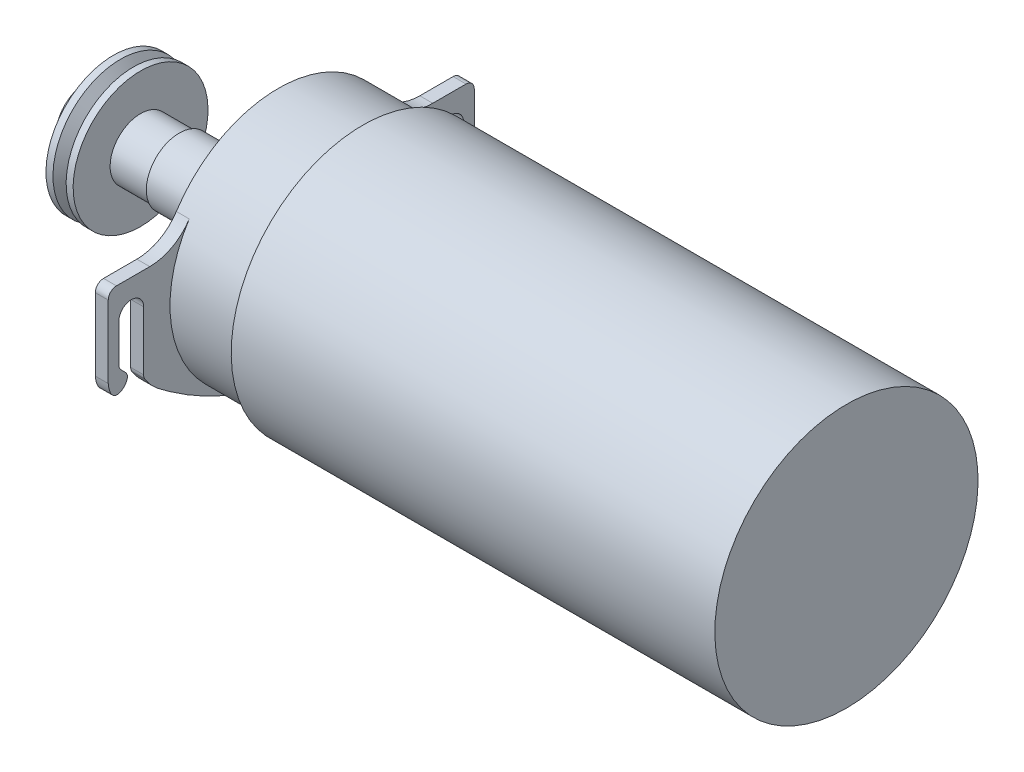
SolidWorks part; units mm, degrees
ref_plane "Front Plane" through (0, 0, 0) normal (0, 0, 1) x (1, 0, 0)
ref_plane "Top Plane" through (0, 0, 0) normal (0, 1, 0) x (1, 0, 0)
ref_plane "Right Plane" through (0, 0, 0) normal (1, 0, 0) x (0, 0, -1)
sketch "Sketch1" plane through (0, 0, 0) normal (0, 0, 1) x (1, 0, 0)
  line L0 (-102.8632, 0.1165) -> (65.8825, 0.1165) construction
  line L1 (65.8825, 0.1165) -> (65.8825, 40.7565)
  line L2 (65.8825, 40.7565) -> (-83.4695, 40.7565)
  line L3 (-83.4695, 40.7565) -> (-83.4695, 37.5561)
  line L4 (-83.4695, 37.5561) -> (-109.5553, 37.5561)
  line L5 (-109.5553, 37.5561) -> (-109.5553, 10.2765)
  line L6 (-109.5553, 10.2765) -> (-140.1623, 10.2765)
  line L7 (-140.1623, 10.2765) -> (-140.1623, 9.5145)
  line L8 (-140.1623, 9.5145) -> (-152.1003, 9.5145)
  line L9 (-152.1003, 9.5145) -> (-152.1003, 20.9445)
  line L10 (-152.1003, 20.9445) -> (-154.2593, 20.9445)
  line L11 (-154.2593, 20.9445) -> (-156.2913, 17.8965)
  line L12 (-156.2913, 27.6325) -> (-156.2913, 11.1433) construction
  line L13 (65.8825, 0.1165) -> (-168.8643, 0.1165)
  line L14 (-160.4823, 9.5145) -> (-160.4823, 20.9445)
  line L15 (-160.4823, 20.9445) -> (-158.3233, 20.9445)
  line L16 (-158.3233, 20.9445) -> (-156.2913, 17.8965)
  line L18 (-160.4823, 9.5145) -> (-162.6413, 9.5145)
  line L19 (-162.6413, 9.5145) -> (-164.6733, 6.4665)
  line L20 (-164.6733, 6.4665) -> (-164.6733, 11.1433) construction
  line L21 (-168.8643, 9.5145) -> (-168.8643, 0.1165)
  line L22 (-168.8643, 9.5145) -> (-166.7053, 9.5145)
  line L23 (-166.7053, 9.5145) -> (-164.6733, 6.4665)
  line L24 (-168.8643, 0.1165) -> (-98.8754, 0.1165) construction
  dimension "D1" = 40.64
  dimension "D2" = 149.352
  dimension "D3" = 26.0858
  dimension "D4" = 20.828
  dimension "D5" = 37.4396
  dimension "D6" = 44.704
  dimension "D7" = 11.938
  dimension "D8" = 2.159
  dimension "D9" = 4.064
  dimension "D11" = 11.43
  dimension "D12" = 10.16
  dimension "D13" = 2.159
  dimension "D14" = 4.064
  dimension "D15" = 3.048
  dimension "D16" = 3.048
revolve "Revolve3" add sketch "Sketch1" angle 360 about L24
sketch "Sketch3" plane through (-109.5553, 0, 0) normal (-1, 0, 0) x (0, 0, 1)
  line L0 (43.6888, 13.7026) -> (53.975, 13.7026)
  line L1 (56.515, 11.1626) -> (56.515, -11.1539)
  line L2 (53.213, -7.8364) -> (53.213, 3.9053)
  line L3 (45.593, 3.9053) -> (45.593, -14.2762)
  line L4 (0, 0.1165) -> (0, 21.1295) construction
  line L5 (-45.593, 3.9053) -> (-45.593, -14.2762)
  line L6 (-53.213, -7.8364) -> (-53.213, 3.9053)
  line L7 (-56.515, 11.1626) -> (-56.515, -11.1539)
  line L8 (-43.6888, 13.7026) -> (-53.975, 13.7026)
  arc A0 (-10.0759, -35.9418) -> (10.0759, -35.9418) centre (0, 0.1165) ccw
  arc A1 (43.6888, 13.7026) -> (31.4944, 20.3606) centre (43.6888, 28.1989) cw
  arc A2 (53.975, 13.7026) -> (56.515, 11.1626) centre (53.975, 11.1626) cw
  arc A3 (53.213, 3.9053) -> (45.593, 3.9053) centre (49.403, 3.9053) ccw
  circle A4 centre (0, 0.1165) radius 37.4396 construction
  arc A5 (45.593, -14.2762) -> (45.2183, -15.6041) centre (43.053, -14.2762) cw
  circle A6 centre (0, 0.1165) radius 20.828 construction
  arc A7 (-43.6888, 13.7026) -> (-31.4944, 20.3606) centre (-43.6888, 28.1989) ccw
  arc A8 (-45.593, -14.2762) -> (-45.2183, -15.6041) centre (-43.053, -14.2762) ccw
  arc A9 (-53.213, 3.9053) -> (-45.593, 3.9053) centre (-49.403, 3.9053) cw
  arc A10 (-53.975, 13.7026) -> (-56.515, 11.1626) centre (-53.975, 11.1626) ccw
  arc A11 (31.4944, 20.3606) -> (-31.4944, 20.3606) centre (0, 0.1165) ccw
  spline S0 degree 3 poles (56.515, -11.1539) (55.7347, -18.9807) (46.8383, -11.9191) (53.2584, -9.5841) (53.213, -7.8364) knots 0 0 0 0 0.643469 1 1 1 1
  spline S1 degree 3 poles (45.2183, -15.6041) (43.4503, -18.487) (32.7585, -26.5922) (21.7852, -32.6698) (10.0759, -35.9418) knots 0.015741 0.015741 0.015741 0.015741 0.236597 1 1 1 1
  spline S2 degree 3 poles (-45.2183, -15.6041) (-43.4503, -18.487) (-32.7585, -26.5922) (-21.7852, -32.6698) (-10.0759, -35.9418) knots 0.015741 0.015741 0.015741 0.015741 0.236597 1 1 1 1
  spline S3 degree 3 poles (-56.515, -11.1539) (-55.7347, -18.9807) (-46.8383, -11.9191) (-53.2584, -9.5841) (-53.213, -7.8364) knots 0 0 0 0 0.643469 1 1 1 1
  dimension "D1" = 2.54
  dimension "D6" = 2.54
  dimension "D2" = 7.62
  dimension "D3" = 35.687
  dimension "D4" = 28.194
  dimension "D5" = 3.302
extrude "Boss-Extrude1" add sketch "Sketch3" against normal blind 3.9878
